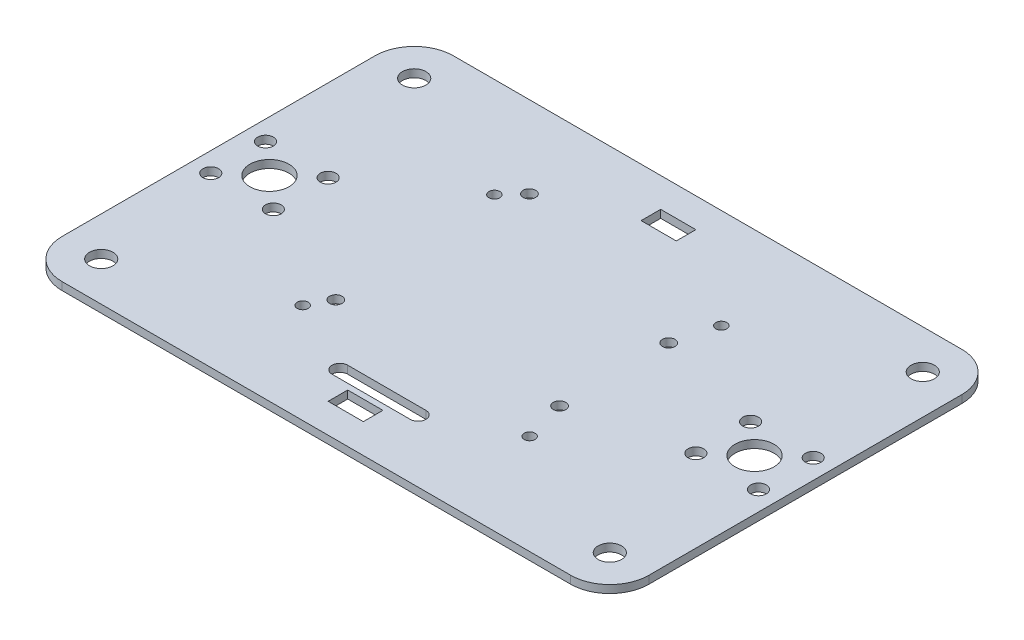
SolidWorks part; units mm, degrees
ref_plane "Front Plane" through (0, 0, 0) normal (0, 0, 1) x (1, 0, 0)
ref_plane "Top Plane" through (0, 0, 0) normal (0, 1, 0) x (1, 0, 0)
ref_plane "Right Plane" through (0, 0, 0) normal (1, 0, 0) x (0, 0, -1)
sketch "Sketch1" plane through (0, 0, 0) normal (0, 1, 0) x (1, 0, 0)
  line L0 (26.1093, 13.95) -> (26.1093, -13.95) construction
  line L1 (-65, -50) -> (65, -50)
  line L2 (-75, -40) -> (-75, 40)
  line L3 (-65, 50) -> (65, 50)
  line L4 (75, -40) -> (75, 40)
  line L5 (-75, -50) -> (75, 50) construction
  line L6 (-75, 50) -> (75, -50) construction
  line L7 (-29, -24.5) -> (29, -24.5) construction
  line L8 (-29, -24.5) -> (-29, 24.5) construction
  line L9 (-29, 24.5) -> (29, 24.5) construction
  line L10 (29, -24.5) -> (29, 24.5) construction
  line L11 (-29, -24.5) -> (29, 24.5) construction
  line L12 (-29, 24.5) -> (29, -24.5) construction
  line L13 (26.1093, -13.95) -> (26.1093, 0) construction
  line L14 (26.1093, 0) -> (-26.1093, 0) construction
  line L15 (-25.9907, -19.05) -> (-26.2907, 29.15) construction
  line L16 (0, 0) -> (0, 50) construction
  line L21 (70, 7) -> (54, -7) construction
  line L22 (-4.5, 42.5) -> (4.5, 42.5)
  line L23 (-4.5, 42.5) -> (-4.5, 37.5)
  line L24 (-4.5, 37.5) -> (4.5, 37.5)
  line L25 (4.5, 42.5) -> (4.5, 37.5)
  line L26 (-4.5, 42.5) -> (4.5, 37.5) construction
  line L27 (-4.5, 37.5) -> (4.5, 42.5) construction
  line L28 (-70, -7) -> (-54, -7) construction
  line L29 (-70, -7) -> (-70, 7) construction
  line L30 (-70, 7) -> (-54, 7) construction
  line L31 (-54, -7) -> (-54, 7) construction
  line L32 (-70, -7) -> (-54, 7) construction
  line L33 (-70, 7) -> (-54, -7) construction
  line L34 (70, -7) -> (54, 7) construction
  line L35 (70, 7) -> (54, 7) construction
  line L36 (54, -7) -> (54, 7) construction
  line L37 (70, -7) -> (54, -7) construction
  line L38 (70, -7) -> (70, 7) construction
  line L39 (-4.5, -37.5) -> (4.5, -42.5) construction
  line L40 (-4.5, -42.5) -> (4.5, -37.5) construction
  line L41 (-4.5, -37.5) -> (4.5, -37.5)
  line L42 (4.5, -42.5) -> (4.5, -37.5)
  line L43 (-4.5, -42.5) -> (-4.5, -37.5)
  line L44 (-4.5, -42.5) -> (4.5, -42.5)
  line L45 (-10, -34) -> (10, -34) construction
  line L46 (-10, -32) -> (10, -32)
  line L47 (-10, -36) -> (10, -36)
  arc A0 (-65, -50) -> (-75, -40) centre (-65, -40) cw
  arc A1 (65, -50) -> (75, -40) centre (65, -40) ccw
  arc A2 (65, 50) -> (75, 40) centre (65, 40) cw
  arc A3 (-75, 40) -> (-65, 50) centre (-65, 40) cw
  circle A4 centre (-29, 24.5) radius 1.4
  circle A6 centre (29, 24.5) radius 1.4
  circle A7 centre (-29, -24.5) radius 1.4
  circle A8 centre (29, -24.5) radius 1.4
  circle A9 centre (-24.6907, 29.15) radius 1.6
  circle A10 centre (-25.9907, -19.05) radius 1.6
  circle A11 centre (26.1093, 13.95) radius 1.6
  circle A12 centre (26.1093, -13.95) radius 1.6
  circle A13 centre (-65, 40) radius 3
  circle A14 centre (65, 40) radius 3
  circle A15 centre (65, -40) radius 3
  circle A16 centre (-65, -40) radius 3
  circle A17 centre (-62, 0) radius 5
  circle A20 centre (-70, 7) radius 2
  circle A21 centre (-54, 7) radius 2
  circle A22 centre (-54, -7) radius 2
  circle A23 centre (-70, -7) radius 2
  circle A24 centre (70, -7) radius 2
  circle A25 centre (70, 7) radius 2
  circle A26 centre (54, -7) radius 2
  circle A27 centre (62, 0) radius 5
  circle A28 centre (54, 7) radius 2
  arc A29 (-10, -32) -> (-10, -36) centre (-10, -34) ccw
  arc A30 (10, -36) -> (10, -32) centre (10, -34) ccw
  point P0 (0, 0)
  point P18 (0, 0)
  point P37 (0, 0)
  point P44 (0, 40)
  point P58 (0, -34)
  point P68 (0, -40)
  point P80 (-4.5, 40)
  point P85 (-4.5, -40)
  dimension "D3" = 10
  dimension "D6" = 2.8
  dimension "D8" = 3.2
  dimension "D13" = 6
  dimension "D14" = 10
  dimension "D19" = 4
  dimension "D1" = 150
  dimension "D2" = 100
  dimension "D4" = 58
  dimension "D5" = 49
  dimension "D7" = 1.3
  dimension "D9" = 15.2
  dimension "D10" = 27.9
  dimension "D11" = 5.1
  dimension "D12" = 50.8
  dimension "D15" = 14
  dimension "D16" = 9
  dimension "D17" = 5
  dimension "D18" = 16
  dimension "D20" = 13
  dimension "D21" = 20
  dimension "D22" = 4
  dimension "D23" = 6
extrude "Boss-Extrude1" add sketch "Sketch1" along normal mid plane 2 contours A3 L2 A0 L1 A1 L4 A2 L3 L22 L25 L24 L23 A4 A6 A7 A8 A9 A10 A11 A12 A13 A14 A15 A16 A17 A20
